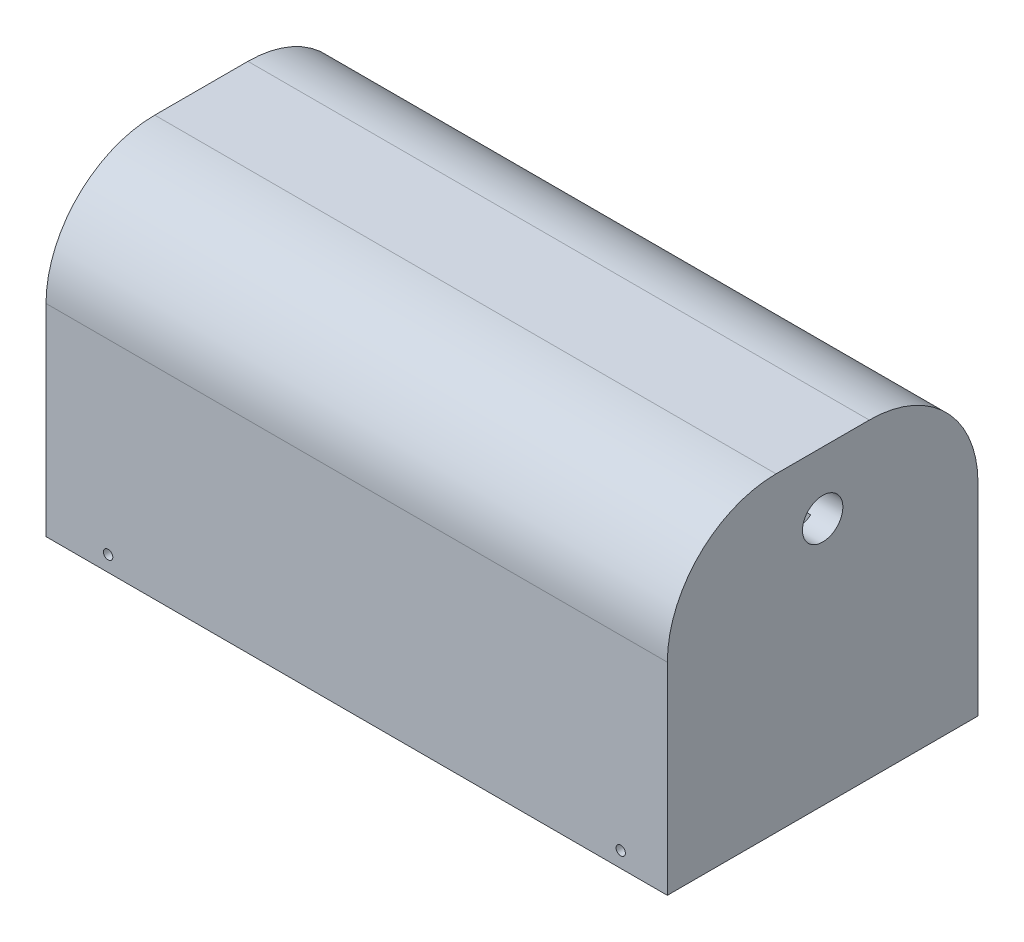
SolidWorks part; units mm, degrees
material "ABS"
ref_plane "Plan de face" through (0, 0, 0) normal (0, 0, 1) x (1, 0, 0)
ref_plane "Plan de dessus" through (0, 0, 0) normal (0, 1, 0) x (1, 0, 0)
ref_plane "Plan de droite" through (0, 0, 0) normal (1, 0, 0) x (0, 0, -1)
sketch "Esquisse1" plane through (0, 0, 0) normal (0, 0, 1) x (1, 0, 0)
  line L1 (100, -50) -> (-100, -50)
  line L2 (100, -50) -> (100, 50)
  line L3 (100, 50) -> (-100, 50)
  line L4 (-100, -50) -> (-100, 50)
  line L5 (100, -50) -> (-100, 50) construction
  line L6 (100, 50) -> (-100, -50) construction
  point P0 (0, 0)
  dimension "D1" = 200
  dimension "D2" = 100
extrude "Boss.-Extru.1" add sketch "Esquisse1" along normal blind 100
sketch "Esquisse2" plane through (100, 0, 0) normal (1, 0, 0) x (0, 0, -1)
  line L0 (-100, 50) -> (0, 50) construction
  line L1 (0, -50) -> (0, 50) construction
  circle A0 centre (-50, 30) radius 6.5
  dimension "D1" = 13
  dimension "D2" = 20
  dimension "D3" = 50
extrude "Enlèv. mat.-Extru.1" cut sketch "Esquisse2" against normal through all
sketch "Esquisse4" plane through (0, 0, 100) normal (0, 0, 1) x (1, 0, 0)
  line L0 (100, -50) -> (100, 50) construction
  line L1 (-100, -50) -> (100, -50) construction
  circle A0 centre (85, -45) radius 1.5
  circle A1 centre (-80, -45) radius 1.5
  dimension "D1" = 3
  dimension "D2" = 15
  dimension "D3" = 5
  dimension "D4" = 180
extrude "Enlèv. mat.-Extru.3" cut sketch "Esquisse4" against normal through all
sketch "Esquisse8" plane through (0, -50, 0) normal (0, -1, 0) x (1, 0, 0)
  line L0 (-100, 0) -> (100, 0) construction
  line L1 (92, 8) -> (-92, 8)
  line L2 (92, 8) -> (92, 92)
  line L3 (92, 92) -> (-92, 92)
  line L4 (-92, 8) -> (-92, 92)
  line L5 (-100, 100) -> (100, 100) construction
  line L6 (100, 100) -> (100, 0) construction
  line L7 (-100, 100) -> (-100, 0) construction
  dimension "D1" = 8
  dimension "D2" = 8
  dimension "D3" = 8
  dimension "D4" = 8
extrude "Enlèv. mat.-Extru.8" cut sketch "Esquisse8" against normal blind 75
sketch "Esquisse9" plane through (0, -50, 0) normal (0, -1, 0) x (1, 0, 0)
  line L0 (100, 100) -> (100, 0) construction
  line L1 (96, 4) -> (-96, 4)
  line L2 (96, 4) -> (96, 96)
  line L3 (96, 96) -> (-96, 96)
  line L4 (-96, 4) -> (-96, 96)
  line L5 (-100, 0) -> (100, 0) construction
  line L6 (-100, 100) -> (100, 100) construction
  line L7 (-100, 100) -> (-100, 0) construction
  dimension "D1" = 4
  dimension "D2" = 4
  dimension "D3" = 4
  dimension "D4" = 4
extrude "Enlèv. mat.-Extru.9" cut sketch "Esquisse9" against normal blind 8
fillet "Congé2" radius 35 2 edges at (0, 50, 0) (0, 50, 100)
